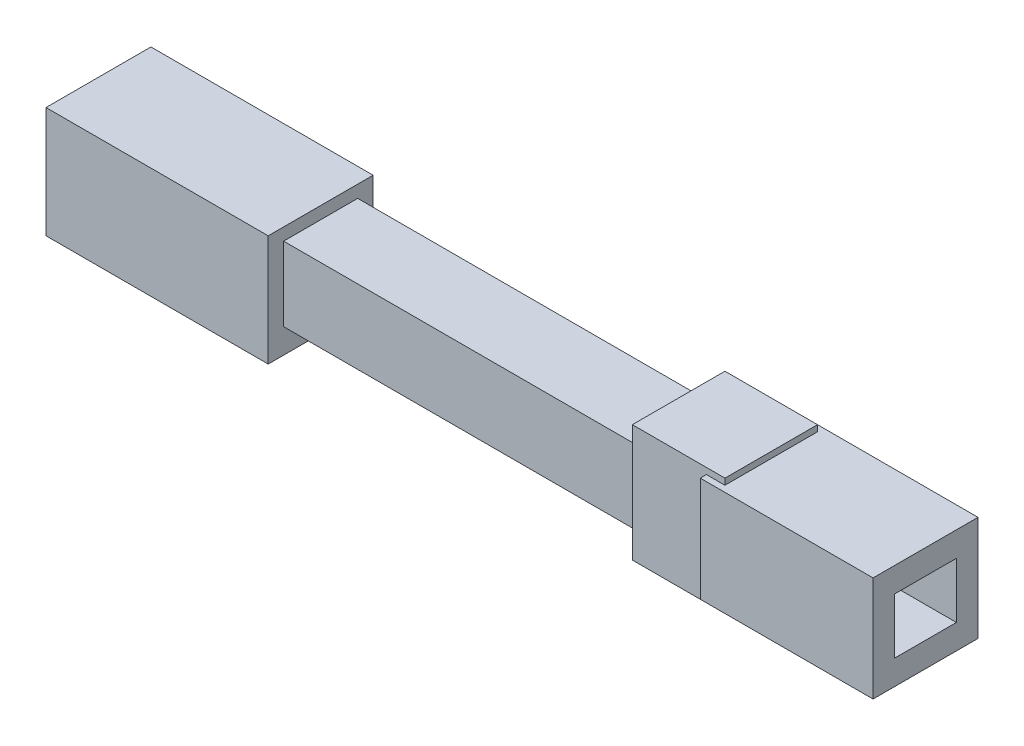
SolidWorks part; units mm, degrees
ref_plane "Front Plane" through (0, 0, 0) normal (0, 0, 1) x (1, 0, 0)
ref_plane "Top Plane" through (0, 0, 0) normal (0, 1, 0) x (1, 0, 0)
ref_plane "Right Plane" through (0, 0, 0) normal (1, 0, 0) x (0, 0, -1)
sketch "Sketch1" plane through (0, 0, 0) normal (0, 0, 1) x (1, 0, 0)
  line L1 (-20, 182) -> (52, 182)
  line L2 (-20, 182) -> (-20, 218)
  line L3 (-20, 218) -> (52, 218)
  line L4 (52, 182) -> (52, 218)
extrude "Boss-Extrude1" add sketch "Sketch1" along normal mid plane 34
sketch "Sketch2" plane through (0, 0, 0) normal (0, 0, 1) x (1, 0, 0)
  line L1 (48, 190) -> (172, 190)
  line L2 (48, 190) -> (48, 214)
  line L3 (48, 214) -> (172, 214)
  line L4 (172, 190) -> (172, 214)
extrude "Boss-Extrude2" add sketch "Sketch2" along normal mid plane 24
sketch "Sketch3" plane through (0, 0, 0) normal (0, 0, 1) x (1, 0, 0)
  line L1 (168, 184) -> (198, 184)
  line L2 (168, 184) -> (168, 222)
  line L3 (168, 222) -> (198, 222)
  line L4 (198, 184) -> (198, 222)
extrude "Boss-Extrude3" add sketch "Sketch3" along normal mid plane 30
sketch "Sketch4" plane through (0, 0, 0) normal (0, 0, 1) x (1, 0, 0)
  line L1 (192, 186) -> (248, 186)
  line L2 (192, 186) -> (192, 220)
  line L3 (192, 220) -> (248, 220)
  line L4 (248, 186) -> (248, 220)
extrude "Boss-Extrude4" add sketch "Sketch4" along normal mid plane 34
sketch "Sketch5" plane through (0, 0, 0) normal (0, 0, 1) x (1, 0, 0)
  line L1 (214, 194) -> (252, 194)
  line L2 (214, 194) -> (214, 212)
  line L3 (214, 212) -> (252, 212)
  line L4 (252, 194) -> (252, 212)
extrude "Cut-Extrude1" cut sketch "Sketch5" against normal mid plane 20
sketch "Sketch6" plane through (0, 0, 0) normal (0, 0, 1) x (1, 0, 0)
  circle A0 centre (0, 198) radius 7.25
extrude "Cut-Extrude2" cut sketch "Sketch6" against normal through all
sketch "Sketch7" plane through (0, 0, 0) normal (0, 0, 1) x (1, 0, 0)
  circle A0 centre (110, 202) radius 7.5
extrude "Cut-Extrude3" cut sketch "Sketch7" against normal through all
